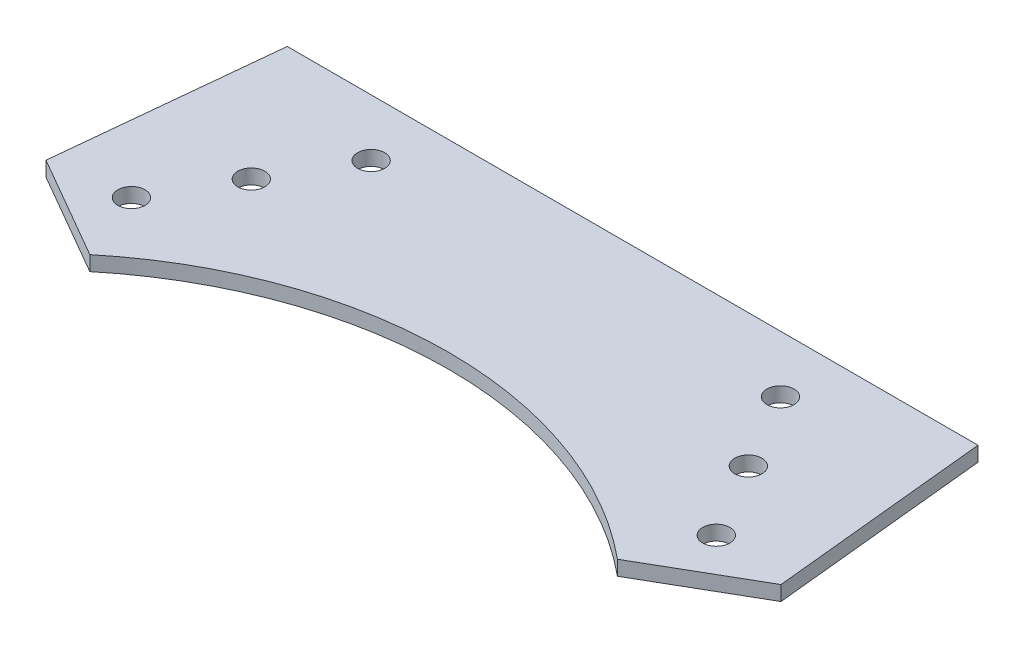
SolidWorks part; units mm, degrees
material "FR4_stuffedProtoboard"
ref_plane "Front Plane" through (0, 0, 0) normal (0, 0, 1) x (1, 0, 0)
ref_plane "Top Plane" through (0, 0, 0) normal (0, 1, 0) x (1, 0, 0)
ref_plane "Right Plane" through (0, 0, 0) normal (1, 0, 0) x (0, 0, -1)
sketch "Sketch1" plane through (0, 0, 0) normal (0, 1, 0) x (1, 0, 0)
  line L0 (-37.5, -32.3215) -> (37.5, -32.3215)
  line L1 (0, 0) -> (-34.2758, -59.3675) construction
  line L2 (0, 0) -> (34.2758, -59.3675) construction
  line L3 (-39.905, -56.1175) -> (-28.6467, -62.6175)
  line L4 (-39.905, -56.1175) -> (-37.5, -32.3215)
  line L5 (0, 0) -> (0, -62.6175) construction
  line L6 (39.905, -56.1175) -> (28.6467, -62.6175)
  line L7 (39.905, -56.1175) -> (37.5, -32.3215)
  arc A0 (-28.6467, -62.6175) -> (28.6467, -62.6175) centre (0, -97.3215) cw
  point P2 (0, -32.3215)
  point P7 (0, -52.3215)
  dimension "D3" = 45
  dimension "D4" = 65
  dimension "D1" = 32.3215
  dimension "D2" = 75
  dimension "D5" = 60
  dimension "D6" = 13
extrude "Boss-Extrude1" add sketch "Sketch1" along normal blind 1.6
hole_wizard "#4 Clearance Hole1" positions "Sketch2" profile "Sketch3" hole size "#4" standard "ANSI Inch" end condition through all
sketch "Sketch2" plane through (0, 1.6, 0) normal (0, 1, 0) x (1, 0, 0)
  line L0 (0, 0) -> (22.225, -38.4948) construction
  line L2 (0, 0) -> (0, -19.1492) construction
  point P0 (22.225, -38.4948)
  point P22 (26.9875, -46.7437)
  point P23 (31.75, -54.9926)
  point P26 (0, 0)
  dimension "D1" = 30
  dimension "D2" = 44.45
  dimension "D4" = 9.525
  dimension "D3" = 3
sketch "Sketch3" plane through (22.225, 1.6, 38.4948) normal (1, 0, 0) x (0, 0, 1)
  line L0 (0, 0) -> (0, 1.6)
  line L1 (0, 1.6) -> (1.4732, 1.6)
  line L2 (1.4732, 1.6) -> (1.4732, 0)
  line L5 (1.4732, 0) -> (0, 0)
  line L11 (0, -6.35) -> (0, 107.95) construction
  dimension "Thru Hole Dia." = 2.9464
  dimension "Thru Hole Depth" = 1.6
mirror "Mirror1" about plane through (0, 0, 0) normal (1, 0, 0) of "#4 Clearance Hole1"
